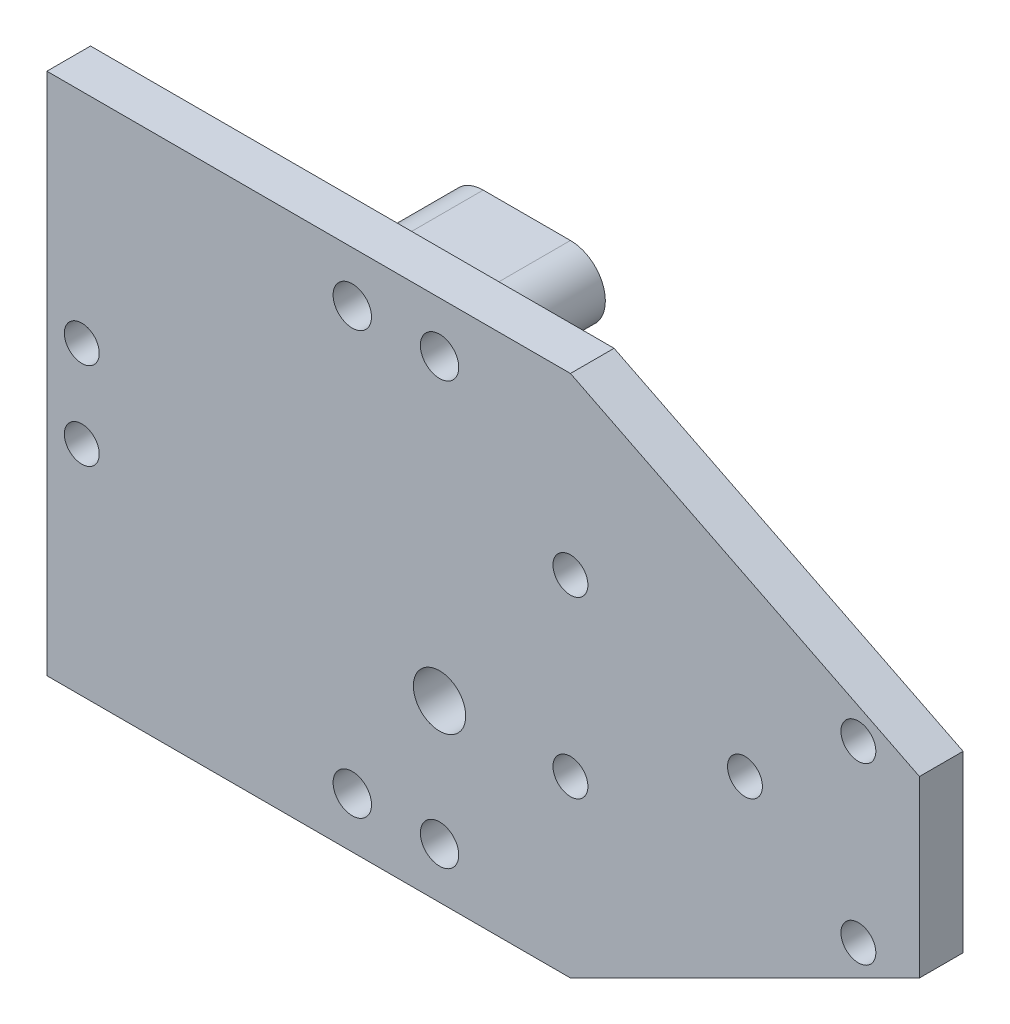
SolidWorks part; units mm, degrees
ref_plane "前视基准面" through (0, 0, 0) normal (0, 0, 1) x (1, 0, 0)
ref_plane "上视基准面" through (0, 0, 0) normal (0, 1, 0) x (1, 0, 0)
ref_plane "右视基准面" through (0, 0, 0) normal (1, 0, 0) x (0, 0, -1)
sketch "草图1" plane through (0, 0, 0) normal (0, 0, 1) x (1, 0, 0)
  line L0 (0, -20) -> (60, -20)
  line L1 (55, 0) -> (-55, 0) construction
  line L2 (60, -20) -> (100, 0)
  line L3 (100, 0) -> (100, 20)
  line L4 (100, 20) -> (60, 40)
  line L5 (60, 40) -> (0, 40)
  line L6 (0, -55) -> (0, 55) construction
  line L7 (0, 40) -> (0, -20)
  circle A0 centre (60, 20) radius 2
  circle A1 centre (60, 0) radius 2
  circle A2 centre (93, 20) radius 2
  circle A3 centre (93, 0) radius 2
  circle A4 centre (45, 0) radius 3
  circle A5 centre (45, 34.2) radius 2.2
  circle A6 centre (45, -14.2) radius 2.2
  circle A7 centre (35, 34.2) radius 2.2
  circle A8 centre (35, -14.2) radius 2.2
  dimension "D1" = 10
  dimension "D2" = 10
extrude "凸台-拉伸1" add sketch "草图1" along normal mid plane 5
sketch "草图2" plane through (0, 0, 0) normal (0, 0, 1) x (1, 0, 0)
  circle A0 centre (80, 10) radius 2
  circle A1 centre (4, 5) radius 2
  circle A2 centre (4, 15) radius 2
extrude "切除-拉伸1" cut sketch "草图2" against normal mid plane 5
sketch "草图3" plane through (0, 0, 2.5) normal (0, 0, 1) x (1, 0, 0)
  line L0 (35, 34.2) -> (45, 34.2) construction
  line L5 (35, 38.2) -> (45, 38.2)
  line L6 (35, 30.2) -> (45, 30.2)
  line L7 (35, -14.2) -> (45, -14.2) construction
  line L8 (35, -10.2) -> (45, -10.2)
  line L9 (35, -18.2) -> (45, -18.2)
  arc A0 (35, 38.2) -> (35, 30.2) centre (35, 34.2) ccw
  arc A1 (45, 30.2) -> (45, 38.2) centre (45, 34.2) ccw
  arc A2 (35, -10.2) -> (35, -18.2) centre (35, -14.2) ccw
  arc A3 (45, -18.2) -> (45, -10.2) centre (45, -14.2) ccw
  circle A4 centre (35, 34.2) radius 2.2
  circle A5 centre (45, 34.2) radius 2.2
  circle A6 centre (35, -14.2) radius 2.2
  circle A7 centre (45, -14.2) radius 2.2
  point P2 (40, 34.2)
  point P13 (40, -14.2)
extrude "凸台-拉伸2" add sketch "草图3" against normal blind 10 from surface at -5 starting at face at (82, 10, -2.5)
